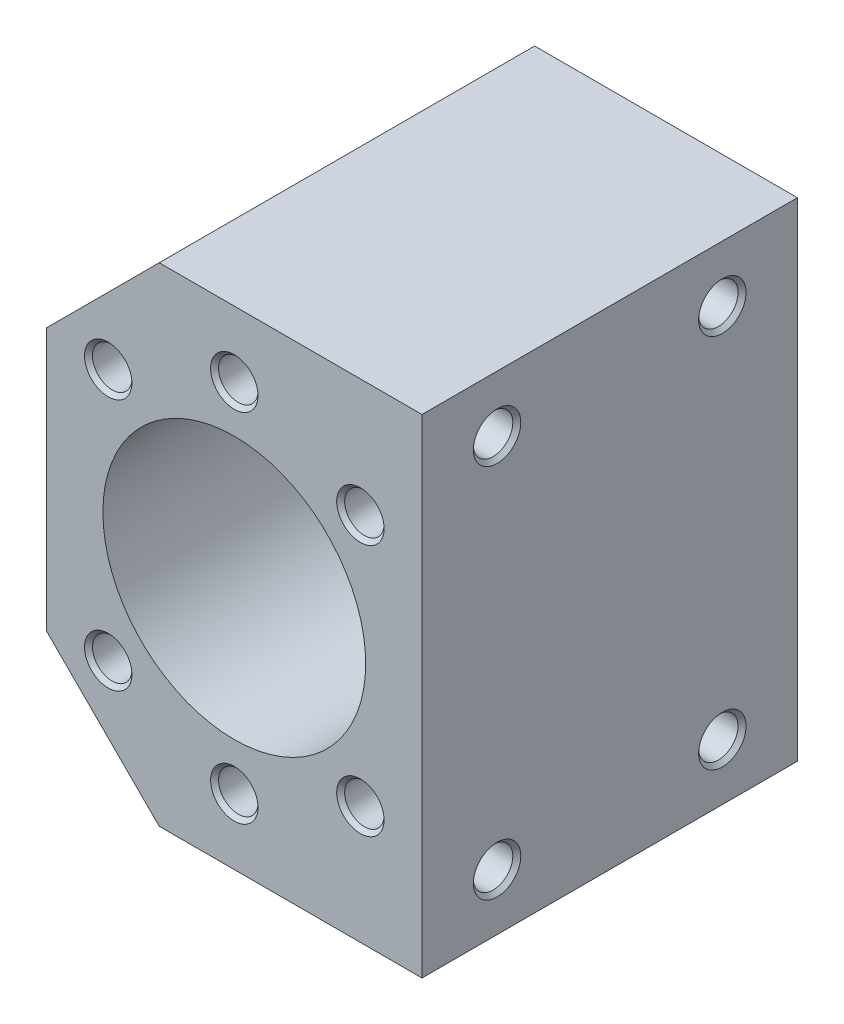
SolidWorks part; units mm, degrees
ref_plane "Front Plane" through (0, 0, 0) normal (0, 0, 1) x (1, 0, 0)
ref_plane "Top Plane" through (0, 0, 0) normal (0, 1, 0) x (1, 0, 0)
ref_plane "Right Plane" through (0, 0, 0) normal (1, 0, 0) x (0, 0, -1)
sketch "Sketch1" plane through (0, 0, 0) normal (0, 0, 1) x (1, 0, 0)
  line L0 (0, -19) -> (0, 19) construction
  line L1 (-20, -26) -> (20, -26)
  line L2 (-20, -26) -> (-20, 26)
  line L3 (-20, 26) -> (20, 26)
  line L4 (20, -26) -> (20, 26)
  line L5 (-20, -26) -> (20, 26) construction
  line L6 (-20, 26) -> (20, -26) construction
  line L7 (0, 0) -> (-13.435, 13.435) construction
  line L8 (0, 0) -> (13.435, 13.435) construction
  line L9 (0, 0) -> (17.8014, 0) construction
  line L10 (0, 0) -> (13.435, -13.435) construction
  line L11 (0, 0) -> (-13.435, -13.435) construction
  circle A0 centre (0, 0) radius 14
  circle A1 centre (0, 0) radius 19 construction
  point P0 (0, 0)
  point P9 (17.8014, 0)
  dimension "D3" = 28
  dimension "D4" = 38
  dimension "D1" = 52
  dimension "D2" = 40
  dimension "D5" = 90
  dimension "D6" = 45
extrude "Boss-Extrude1" add sketch "Sketch1" along normal mid plane 40
hole_wizard "M5x0.8 Tapped Hole1" positions "Sketch2" profile "Sketch3" tap size "M5x0.8" standard "ANSI Metric"
sketch "Sketch2" plane through (0, 0, 20) normal (0, 0, 1) x (1, 0, 0)
  point P0 (-13.435, 13.435)
  point P3 (0, 19)
  point P6 (13.435, 13.435)
  point P9 (13.435, -13.435)
  point P12 (0, -19)
  point P15 (-13.435, -13.435)
sketch "Sketch3" plane through (-13.435, 13.435, 20) normal (1, 0, 0) x (0, -1, 0)
  line L0 (0, 0) -> (0, 11.2618)
  line L1 (0, 11.2618) -> (2.1, 10)
  line L2 (2.1, 10) -> (2.1, 0.425)
  line L3 (2.1, 0.425) -> (2.525, 0)
  line L5 (2.525, 0) -> (0, 0)
  line L6 (-2.1, 0.425) -> (-2.525, 0) construction
  line L10 (0, 11.2618) -> (-2.1, 10) construction
  line L11 (0, -6.35) -> (0, 107.95) construction
  dimension "Tap Drill Dia." = 4.2
  dimension "Tap Drill Depth" = 10
  dimension "Near C'Sink Dia." = 5.05
  dimension "Near C'Sink Angle" = 90
  dimension "Drill Angle" = 118
chamfer "Chamfer1" distance 12 angle 45 2 edges at (-20, -26, 0) (-20, 26, 0)
sketch "Sketch4" plane through (20, 0, 0) normal (1, 0, 0) x (0, 0, -1)
  line L0 (0, 0) -> (12, 0) construction
  line L1 (12, 20) -> (-12, 20) construction
  line L2 (12, 20) -> (12, -20) construction
  line L3 (12, -20) -> (-12, -20) construction
  line L4 (-12, 20) -> (-12, -20) construction
  line L5 (-20, -26) -> (-20, 26) construction
  dimension "D1" = 40
  dimension "D2" = 24
  dimension "D3" = 8
hole_wizard "M5x0.8 Tapped Hole2" positions "Sketch5" profile "Sketch6" tap size "M5x0.8" standard "ANSI Metric"
sketch "Sketch5" plane through (20, 0, 0) normal (1, 0, 0) x (0, 0, -1)
  point P0 (-12, 20)
  point P3 (12, 20)
  point P6 (12, -20)
  point P9 (-12, -20)
sketch "Sketch6" plane through (20, 20, 12) normal (0, 1, 0) x (0, 0, -1)
  line L0 (0, 0) -> (0, 13.6618)
  line L1 (0, 13.6618) -> (2.1, 12.4)
  line L2 (2.1, 12.4) -> (2.1, 0.425)
  line L3 (2.1, 0.425) -> (2.525, 0)
  line L5 (2.525, 0) -> (0, 0)
  line L6 (-2.1, 0.425) -> (-2.525, 0) construction
  line L10 (0, 13.6618) -> (-2.1, 12.4) construction
  line L11 (0, -6.35) -> (0, 107.95) construction
  dimension "Tap Drill Dia." = 4.2
  dimension "Tap Drill Depth" = 12.4
  dimension "Near C'Sink Dia." = 5.05
  dimension "Near C'Sink Angle" = 90
  dimension "Drill Angle" = 118
